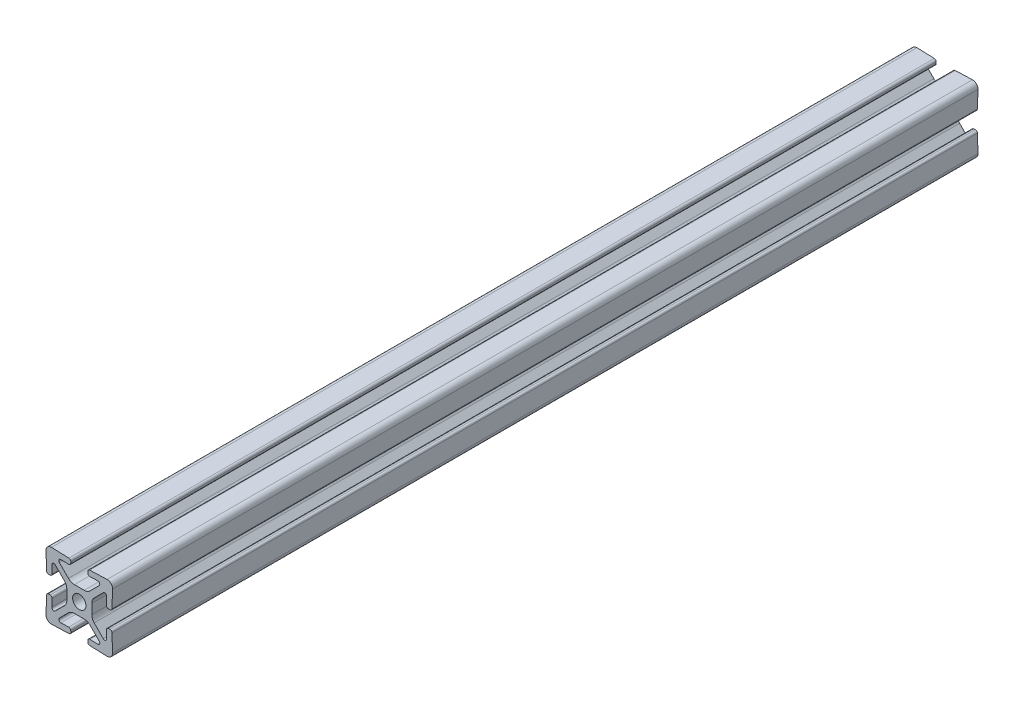
SolidWorks part; units mm, degrees
ref_plane "Front Plane" through (0, 0, 0) normal (0, 0, 1) x (1, 0, 0)
ref_plane "Top Plane" through (0, 0, 0) normal (0, 1, 0) x (1, 0, 0)
ref_plane "Right Plane" through (0, 0, 0) normal (1, 0, 0) x (0, 0, -1)
sketch "Sketch1" plane through (0, 0, 0) normal (0, 0, 1) x (1, 0, 0)
  line L0 (0, 0) -> (0, 12.7) construction
  line L1 (0, 0) -> (12.7, 0) construction
  line L2 (0, 0) -> (-12.7, 12.7) construction
  line L3 (-10.5971, 12.6988) -> (-3.9739, 12.4675)
  line L4 (-12.7, 12.7) -> (0, 12.7) construction
  line L6 (-4.0475, 10.3606) -> (-7.0332, 10.4648)
  line L10 (0, 4.7625) -> (-1.8848, 4.7625)
  line L11 (-4.1299, 5.6924) -> (-7.5996, 9.1622)
  line L24 (0, 0) -> (-12.7, 0) construction
  line L25 (-12.7, 0) -> (0, 0) construction
  line L26 (0, 0) -> (0, -12.7) construction
  line L27 (-12.7, -12.7) -> (-12.7, 12.7) construction
  line L28 (0, 12.7) -> (12.7, 12.7) construction
  line L29 (-3.239, 11.6793) -> (-3.2594, 11.0955)
  line L30 (-12.7, -12.7) -> (12.7, -12.7) construction
  arc A0 (-12.1048, 12.1048) -> (-10.5971, 12.6988) centre (-10.668, 10.668) cw
  arc A6 (-1.8848, 4.7625) -> (-4.1299, 5.6924) centre (-1.8848, 7.9375) cw
  circle A16 centre (0, 0) radius 2.54
  arc A18 (-7.5996, 9.1622) -> (-7.0332, 10.4648) centre (-7.0599, 9.702) cw
  circle A19 centre (-2.3794, 2.3794) radius 0.635 construction
  arc A20 (-4.0475, 10.3606) -> (-3.2594, 11.0955) centre (-4.0209, 11.1221) ccw
  arc A21 (-3.9739, 12.4675) -> (-3.239, 11.6793) centre (-4.0005, 11.7059) cw
  point P15 (0, 0)
  point P42 (-3.1999, 4.7625)
  point P80 (-12.7, 0)
  point P85 (0, -12.7)
  point P88 (0, -12.7)
  dimension "D11" = 2.032
  dimension "D15" = 3.175
  dimension "Center Hole Diameter" = 5.08
  dimension "D6" = 1.27
  dimension "D4" = 0.7633
  dimension "D8" = 0.762
  dimension "D12" = 0.762
  dimension "D1" = 45
  dimension "D2" = 2
  dimension "Rail Width" = 25.4
  dimension "D10" = 2.2098
  dimension "T-Slot Depth" = 7.9375
  dimension "D9" = 2.1082
  dimension "Rail Height" = 25.4
  dimension "D23" = 9.525
  dimension "D5" = 15.6464
  dimension "D3" = 4
  dimension "D7" = 5.7028
  dimension "T-Slot Width" = 6.477
sketch "Sketch2" plane through (0, 0, 0) normal (1, 0, 0) x (0, 0, -1)
  line L0 (-609.6, 0) -> (609.6, 0)
  line L2 (0, 0) -> (0, 12.7) construction
  line L3 (0, 0) -> (0, 12.7) construction
  point P0 (-571.5, 0)
  point P3 (0, 0)
  point P7 (571.5, 0)
  dimension "D1" = 38.1
  dimension "Length" = 1219.2
sketch "Sketch3" plane through (0, 0, 0) normal (0, 0, 1) x (1, 0, 0)
  line L2 (0, 4.7625) -> (-1.8848, 4.7625) construction
  line L5 (-4.1299, 5.6924) -> (-7.5996, 9.1622) construction
  line L6 (-4.0475, 10.3606) -> (-7.0332, 10.4648) construction
  line L7 (-3.239, 11.6793) -> (-3.2594, 11.0955) construction
  line L67 (-10.5971, 12.6988) -> (-3.9739, 12.4675) construction
  line L68 (0, 4.7625) -> (-1.8848, 4.7625)
  line L69 (-4.1299, 5.6924) -> (-7.5996, 9.1622)
  line L70 (-4.0475, 10.3606) -> (-7.0332, 10.4648)
  line L71 (-3.239, 11.6793) -> (-3.2594, 11.0955)
  line L72 (-10.5971, 12.6988) -> (-3.9739, 12.4675)
  line L73 (0, 0) -> (-12.7, 12.7) construction
  line L74 (0, 0) -> (-12.7, 12.7) construction
  line L75 (-12.6988, 10.5971) -> (-12.4675, 3.9739)
  line L76 (-11.6793, 3.239) -> (-11.0955, 3.2594)
  line L77 (-10.3606, 4.0475) -> (-10.4648, 7.0332)
  line L78 (-5.6924, 4.1299) -> (-9.1622, 7.5996)
  line L79 (-4.7625, 0) -> (-4.7625, 1.8848)
  line L80 (-4.7625, 0) -> (-2.54, 0)
  line L82 (0, 4.7625) -> (0, 2.54)
  arc A3 (-4.1299, 5.6924) -> (-1.8848, 4.7625) centre (-1.8848, 7.9375) ccw construction
  circle A10 centre (0, 0) radius 2.54
  arc A56 (0, 2.54) -> (-2.54, 0) centre (0, 0) ccw
  arc A57 (-7.0332, 10.4648) -> (-7.5996, 9.1622) centre (-7.0599, 9.702) ccw construction
  arc A58 (-4.0475, 10.3606) -> (-3.2594, 11.0955) centre (-4.0209, 11.1221) ccw construction
  arc A59 (-3.239, 11.6793) -> (-3.9739, 12.4675) centre (-4.0005, 11.7059) ccw construction
  arc A60 (-10.5971, 12.6988) -> (-12.1048, 12.1048) centre (-10.668, 10.668) ccw construction
  arc A61 (-4.1299, 5.6924) -> (-1.8848, 4.7625) centre (-1.8848, 7.9375) ccw
  arc A62 (-7.0332, 10.4648) -> (-7.5996, 9.1622) centre (-7.0599, 9.702) ccw
  arc A63 (-4.0475, 10.3606) -> (-3.2594, 11.0955) centre (-4.0209, 11.1221) ccw
  arc A64 (-3.239, 11.6793) -> (-3.9739, 12.4675) centre (-4.0005, 11.7059) ccw
  arc A65 (-10.5971, 12.6988) -> (-12.6988, 10.5971) centre (-10.668, 10.668) ccw
  arc A67 (-11.6793, 3.239) -> (-12.4675, 3.9739) centre (-11.7059, 4.0005) cw
  arc A68 (-10.3606, 4.0475) -> (-11.0955, 3.2594) centre (-11.1221, 4.0209) cw
  arc A69 (-10.4648, 7.0332) -> (-9.1622, 7.5996) centre (-9.702, 7.0599) cw
  arc A70 (-5.6924, 4.1299) -> (-4.7625, 1.8848) centre (-7.9375, 1.8848) cw
  dimension "D1" = 0
extrude "Boss-Extrude1" add sketch "Sketch3" along normal mid plane 1219.2
pattern_circular "CirPattern1" count 4 over 360 about axis through (0, 0, 0) along (0, 0, 1) of "Boss-Extrude1"
ref_plane "Contact Plane 1" through (0, 12.7, 0) normal (0, 1, 0) x (1, 0, 0)
ref_plane "Contact Plane 2" through (12.7, 0, 0) normal (1, 0, 0) x (0, 0, -1)
ref_plane "Contact Plane 3" through (0, -12.7, 0) normal (0, -1, 0) x (-1, 0, 0)
ref_plane "Contact Plane 4" through (-12.7, 0, 0) normal (-1, 0, 0) x (0, 0, 1)
sketch "Sketch4" plane through (0, 0, 609.6) normal (0, 0, 1) x (1, 0, 0)
  line L36 (1.8848, 4.7625) -> (-1.8848, 4.7625)
  line L37 (-4.1299, 5.6924) -> (-7.5996, 9.1622)
  line L38 (-7.0332, 10.4648) -> (-4.0475, 10.3606)
  line L39 (-3.2594, 11.0955) -> (-3.239, 11.6793)
  line L40 (-3.9739, 12.4675) -> (-10.5971, 12.6988)
  line L41 (-12.6988, 10.5971) -> (-12.4675, 3.9739)
  line L42 (-11.6793, 3.239) -> (-11.0955, 3.2594)
  line L43 (-10.3606, 4.0475) -> (-10.4648, 7.0332)
  line L44 (-9.1622, 7.5996) -> (-5.6924, 4.1299)
  line L45 (-4.7625, 1.8848) -> (-4.7625, -1.8848)
  line L46 (-5.6924, -4.1299) -> (-9.1622, -7.5996)
  line L47 (-10.4648, -7.0332) -> (-10.3606, -4.0475)
  line L48 (-11.0955, -3.2594) -> (-11.6793, -3.239)
  line L49 (-12.4675, -3.9739) -> (-12.6988, -10.5971)
  line L50 (-10.5971, -12.6988) -> (-3.9739, -12.4675)
  line L51 (-3.239, -11.6793) -> (-3.2594, -11.0955)
  line L52 (-4.0475, -10.3606) -> (-7.0332, -10.4648)
  line L53 (-7.5996, -9.1622) -> (-4.1299, -5.6924)
  line L54 (-1.8848, -4.7625) -> (1.8848, -4.7625)
  line L55 (4.1299, -5.6924) -> (7.5996, -9.1622)
  line L56 (7.0332, -10.4648) -> (4.0475, -10.3606)
  line L57 (3.2594, -11.0955) -> (3.239, -11.6793)
  line L58 (3.9739, -12.4675) -> (10.5971, -12.6988)
  line L59 (12.6988, -10.5971) -> (12.4675, -3.9739)
  line L60 (11.6793, -3.239) -> (11.0955, -3.2594)
  line L61 (10.3606, -4.0475) -> (10.4648, -7.0332)
  line L62 (9.1622, -7.5996) -> (5.6924, -4.1299)
  line L63 (4.7625, -1.8848) -> (4.7625, 1.8848)
  line L64 (5.6924, 4.1299) -> (9.1622, 7.5996)
  line L65 (10.4648, 7.0332) -> (10.3606, 4.0475)
  line L66 (11.0955, 3.2594) -> (11.6793, 3.239)
  line L67 (12.4675, 3.9739) -> (12.6988, 10.5971)
  line L68 (10.5971, 12.6988) -> (3.9739, 12.4675)
  line L69 (3.239, 11.6793) -> (3.2594, 11.0955)
  line L70 (4.0475, 10.3606) -> (7.0332, 10.4648)
  line L71 (7.5996, 9.1622) -> (4.1299, 5.6924)
  line L72 (1.8848, 4.7625) -> (-1.8848, 4.7625)
  line L73 (-4.1299, 5.6924) -> (-7.5996, 9.1622)
  line L74 (-7.0332, 10.4648) -> (-4.0475, 10.3606)
  line L75 (-3.2594, 11.0955) -> (-3.239, 11.6793)
  line L76 (-3.9739, 12.4675) -> (-10.5971, 12.6988)
  line L77 (-12.6988, 10.5971) -> (-12.4675, 3.9739)
  line L78 (-11.6793, 3.239) -> (-11.0955, 3.2594)
  line L79 (-10.3606, 4.0475) -> (-10.4648, 7.0332)
  line L80 (-9.1622, 7.5996) -> (-5.6924, 4.1299)
  line L81 (-4.7625, 1.8848) -> (-4.7625, -1.8848)
  line L82 (-5.6924, -4.1299) -> (-9.1622, -7.5996)
  line L83 (-10.4648, -7.0332) -> (-10.3606, -4.0475)
  line L84 (-11.0955, -3.2594) -> (-11.6793, -3.239)
  line L85 (-12.4675, -3.9739) -> (-12.6988, -10.5971)
  line L86 (-10.5971, -12.6988) -> (-3.9739, -12.4675)
  line L87 (-3.239, -11.6793) -> (-3.2594, -11.0955)
  line L88 (-4.0475, -10.3606) -> (-7.0332, -10.4648)
  line L89 (-7.5996, -9.1622) -> (-4.1299, -5.6924)
  line L90 (-1.8848, -4.7625) -> (1.8848, -4.7625)
  line L91 (4.1299, -5.6924) -> (7.5996, -9.1622)
  line L92 (7.0332, -10.4648) -> (4.0475, -10.3606)
  line L93 (3.2594, -11.0955) -> (3.239, -11.6793)
  line L94 (3.9739, -12.4675) -> (10.5971, -12.6988)
  line L95 (12.6988, -10.5971) -> (12.4675, -3.9739)
  line L96 (11.6793, -3.239) -> (11.0955, -3.2594)
  line L97 (10.3606, -4.0475) -> (10.4648, -7.0332)
  line L98 (9.1622, -7.5996) -> (5.6924, -4.1299)
  line L99 (4.7625, -1.8848) -> (4.7625, 1.8848)
  line L100 (5.6924, 4.1299) -> (9.1622, 7.5996)
  line L101 (10.4648, 7.0332) -> (10.3606, 4.0475)
  line L102 (11.0955, 3.2594) -> (11.6793, 3.239)
  line L103 (12.4675, 3.9739) -> (12.6988, 10.5971)
  line L104 (10.5971, 12.6988) -> (3.9739, 12.4675)
  line L105 (3.239, 11.6793) -> (3.2594, 11.0955)
  line L106 (4.0475, 10.3606) -> (7.0332, 10.4648)
  line L107 (7.5996, 9.1622) -> (4.1299, 5.6924)
  arc A36 (1.8848, 4.7625) -> (4.1299, 5.6924) centre (1.8848, 7.9375) ccw
  arc A37 (-4.1299, 5.6924) -> (-1.8848, 4.7625) centre (-1.8848, 7.9375) ccw
  arc A38 (-7.0332, 10.4648) -> (-7.5996, 9.1622) centre (-7.0599, 9.702) ccw
  arc A39 (-4.0475, 10.3606) -> (-3.2594, 11.0955) centre (-4.0209, 11.1221) ccw
  arc A40 (-3.239, 11.6793) -> (-3.9739, 12.4675) centre (-4.0005, 11.7059) ccw
  arc A41 (-10.5971, 12.6988) -> (-12.6988, 10.5971) centre (-10.668, 10.668) ccw
  arc A42 (-12.4675, 3.9739) -> (-11.6793, 3.239) centre (-11.7059, 4.0005) ccw
  arc A43 (-11.0955, 3.2594) -> (-10.3606, 4.0475) centre (-11.1221, 4.0209) ccw
  arc A44 (-9.1622, 7.5996) -> (-10.4648, 7.0332) centre (-9.702, 7.0599) ccw
  arc A45 (-4.7625, 1.8848) -> (-5.6924, 4.1299) centre (-7.9375, 1.8848) ccw
  arc A46 (-5.6924, -4.1299) -> (-4.7625, -1.8848) centre (-7.9375, -1.8848) ccw
  arc A47 (-10.4648, -7.0332) -> (-9.1622, -7.5996) centre (-9.702, -7.0599) ccw
  arc A48 (-10.3606, -4.0475) -> (-11.0955, -3.2594) centre (-11.1221, -4.0209) ccw
  arc A49 (-11.6793, -3.239) -> (-12.4675, -3.9739) centre (-11.7059, -4.0005) ccw
  arc A50 (-12.6988, -10.5971) -> (-10.5971, -12.6988) centre (-10.668, -10.668) ccw
  arc A51 (-3.9739, -12.4675) -> (-3.239, -11.6793) centre (-4.0005, -11.7059) ccw
  arc A52 (-3.2594, -11.0955) -> (-4.0475, -10.3606) centre (-4.0209, -11.1221) ccw
  arc A53 (-7.5996, -9.1622) -> (-7.0332, -10.4648) centre (-7.0599, -9.702) ccw
  arc A54 (-1.8848, -4.7625) -> (-4.1299, -5.6924) centre (-1.8848, -7.9375) ccw
  arc A55 (4.1299, -5.6924) -> (1.8848, -4.7625) centre (1.8848, -7.9375) ccw
  arc A56 (7.0332, -10.4648) -> (7.5996, -9.1622) centre (7.0599, -9.702) ccw
  arc A57 (4.0475, -10.3606) -> (3.2594, -11.0955) centre (4.0209, -11.1221) ccw
  arc A58 (3.239, -11.6793) -> (3.9739, -12.4675) centre (4.0005, -11.7059) ccw
  arc A59 (10.5971, -12.6988) -> (12.6988, -10.5971) centre (10.668, -10.668) ccw
  arc A60 (12.4675, -3.9739) -> (11.6793, -3.239) centre (11.7059, -4.0005) ccw
  arc A61 (11.0955, -3.2594) -> (10.3606, -4.0475) centre (11.1221, -4.0209) ccw
  arc A62 (9.1622, -7.5996) -> (10.4648, -7.0332) centre (9.702, -7.0599) ccw
  arc A63 (4.7625, -1.8848) -> (5.6924, -4.1299) centre (7.9375, -1.8848) ccw
  arc A64 (5.6924, 4.1299) -> (4.7625, 1.8848) centre (7.9375, 1.8848) ccw
  arc A65 (10.4648, 7.0332) -> (9.1622, 7.5996) centre (9.702, 7.0599) ccw
  arc A66 (10.3606, 4.0475) -> (11.0955, 3.2594) centre (11.1221, 4.0209) ccw
  arc A67 (11.6793, 3.239) -> (12.4675, 3.9739) centre (11.7059, 4.0005) ccw
  arc A68 (12.6988, 10.5971) -> (10.5971, 12.6988) centre (10.668, 10.668) ccw
  arc A69 (3.9739, 12.4675) -> (3.239, 11.6793) centre (4.0005, 11.7059) ccw
  arc A70 (3.2594, 11.0955) -> (4.0475, 10.3606) centre (4.0209, 11.1221) ccw
  arc A71 (7.5996, 9.1622) -> (7.0332, 10.4648) centre (7.0599, 9.702) ccw
  arc A72 (1.8848, 4.7625) -> (4.1299, 5.6924) centre (1.8848, 7.9375) ccw
  arc A73 (-4.1299, 5.6924) -> (-1.8848, 4.7625) centre (-1.8848, 7.9375) ccw
  arc A74 (-7.0332, 10.4648) -> (-7.5996, 9.1622) centre (-7.0599, 9.702) ccw
  arc A75 (-4.0475, 10.3606) -> (-3.2594, 11.0955) centre (-4.0209, 11.1221) ccw
  arc A76 (-3.239, 11.6793) -> (-3.9739, 12.4675) centre (-4.0005, 11.7059) ccw
  arc A77 (-10.5971, 12.6988) -> (-12.6988, 10.5971) centre (-10.668, 10.668) ccw
  arc A78 (-12.4675, 3.9739) -> (-11.6793, 3.239) centre (-11.7059, 4.0005) ccw
  arc A79 (-11.0955, 3.2594) -> (-10.3606, 4.0475) centre (-11.1221, 4.0209) ccw
  arc A80 (-9.1622, 7.5996) -> (-10.4648, 7.0332) centre (-9.702, 7.0599) ccw
  arc A81 (-4.7625, 1.8848) -> (-5.6924, 4.1299) centre (-7.9375, 1.8848) ccw
  arc A82 (-5.6924, -4.1299) -> (-4.7625, -1.8848) centre (-7.9375, -1.8848) ccw
  arc A83 (-10.4648, -7.0332) -> (-9.1622, -7.5996) centre (-9.702, -7.0599) ccw
  arc A84 (-10.3606, -4.0475) -> (-11.0955, -3.2594) centre (-11.1221, -4.0209) ccw
  arc A85 (-11.6793, -3.239) -> (-12.4675, -3.9739) centre (-11.7059, -4.0005) ccw
  arc A86 (-12.6988, -10.5971) -> (-10.5971, -12.6988) centre (-10.668, -10.668) ccw
  arc A87 (-3.9739, -12.4675) -> (-3.239, -11.6793) centre (-4.0005, -11.7059) ccw
  arc A88 (-3.2594, -11.0955) -> (-4.0475, -10.3606) centre (-4.0209, -11.1221) ccw
  arc A89 (-7.5996, -9.1622) -> (-7.0332, -10.4648) centre (-7.0599, -9.702) ccw
  arc A90 (-1.8848, -4.7625) -> (-4.1299, -5.6924) centre (-1.8848, -7.9375) ccw
  arc A91 (4.1299, -5.6924) -> (1.8848, -4.7625) centre (1.8848, -7.9375) ccw
  arc A92 (7.0332, -10.4648) -> (7.5996, -9.1622) centre (7.0599, -9.702) ccw
  arc A93 (4.0475, -10.3606) -> (3.2594, -11.0955) centre (4.0209, -11.1221) ccw
  arc A94 (3.239, -11.6793) -> (3.9739, -12.4675) centre (4.0005, -11.7059) ccw
  arc A95 (10.5971, -12.6988) -> (12.6988, -10.5971) centre (10.668, -10.668) ccw
  arc A96 (12.4675, -3.9739) -> (11.6793, -3.239) centre (11.7059, -4.0005) ccw
  arc A97 (11.0955, -3.2594) -> (10.3606, -4.0475) centre (11.1221, -4.0209) ccw
  arc A98 (9.1622, -7.5996) -> (10.4648, -7.0332) centre (9.702, -7.0599) ccw
  arc A99 (4.7625, -1.8848) -> (5.6924, -4.1299) centre (7.9375, -1.8848) ccw
  arc A100 (5.6924, 4.1299) -> (4.7625, 1.8848) centre (7.9375, 1.8848) ccw
  arc A101 (10.4648, 7.0332) -> (9.1622, 7.5996) centre (9.702, 7.0599) ccw
  arc A102 (10.3606, 4.0475) -> (11.0955, 3.2594) centre (11.1221, 4.0209) ccw
  arc A103 (11.6793, 3.239) -> (12.4675, 3.9739) centre (11.7059, 4.0005) ccw
  arc A104 (12.6988, 10.5971) -> (10.5971, 12.6988) centre (10.668, 10.668) ccw
  arc A105 (3.9739, 12.4675) -> (3.239, 11.6793) centre (4.0005, 11.7059) ccw
  arc A106 (3.2594, 11.0955) -> (4.0475, 10.3606) centre (4.0209, 11.1221) ccw
  arc A107 (7.5996, 9.1622) -> (7.0332, 10.4648) centre (7.0599, 9.702) ccw
  dimension "D1" = 0
extrude "Cut-Extrude1" cut sketch "Sketch4" against normal offset from surface (889 mm away) 330.2
equation "\"D1@Sketch2\"=\"Rail Width@Sketch1\"*1.5"
equation "\"D1@Boss-Extrude1\"=\"Length@Sketch2\""
